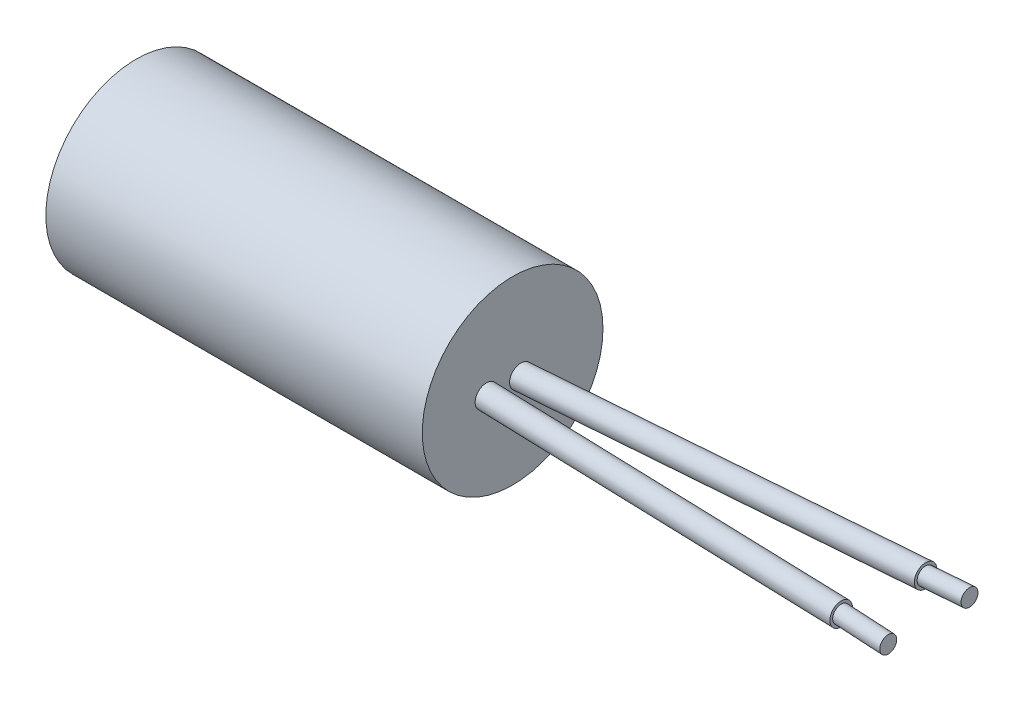
SolidWorks part; units mm, degrees
ref_plane "Front Plane" through (0, 0, 0) normal (0, 0, 1) x (1, 0, 0)
ref_plane "Top Plane" through (0, 0, 0) normal (0, 1, 0) x (1, 0, 0)
ref_plane "Right Plane" through (0, 0, 0) normal (1, 0, 0) x (0, 0, -1)
sketch "Sketch1" plane through (0, 0, 0) normal (1, 0, 0) x (0, 0, -1)
  circle A0 centre (0, 0) radius 4.8
  dimension "D1" = 9.6
extrude "Tube" add sketch "Sketch1" along normal blind 20
sketch "Sketch2" plane through (0, 0, 0) normal (0, 1, 0) x (1, 0, 0)
  line L0 (20, -4.8) -> (20, 4.8) construction
  line L2 (39.9389, 2) -> (39.9389, 0) construction
  line L3 (39.9389, 0) -> (39.9389, -3.1987) construction
  line L4 (39.9389, 0) -> (20, 0) construction
  spline S0 degree 1 poles (20, 0.4375) (39.9389, 2) knots 0 0 1 1
  dimension "D1" = 20
  dimension "D2" = 2
sketch "Sketch3" plane through (20, 0, 0) normal (1, 0, 0) x (0, 0, -1)
  circle A1 centre (0.4375, 0) radius 0.6
sweep "Sweep1" add profiles "Sketch3" path "Sketch2"
sketch "Sketch5" plane through (0, 0, 0) normal (0, 1, 0) x (1, 0, 0)
  line L0 (20, -1.3925) -> (39.4528, -2)
  line L1 (20, -4.8) -> (20, 4.8) construction
  line L2 (39.4528, -2) -> (39.4528, 0) construction
  line L3 (39.4528, 0) -> (20, 0) construction
  dimension "D1" = 2
sketch "Sketch6" plane through (20, 0, 0) normal (1, 0, 0) x (0, 0, -1)
  circle A0 centre (-1.3925, 0) radius 0.6
sweep "Sweep2" add profiles "Sketch6" path "Sketch5"
sketch "Sketch7" plane through (0, 0, 0) normal (0, 1, 0) x (1, 0, 0)
  line L0 (39.9389, 2) -> (52.6031, 2.9989)
  line L1 (39.9389, 1.4) -> (39.9389, 2.6) construction
sketch "Sketch8" plane through (0, 0, 0) normal (0, 1, 0) x (1, 0, 0)
  line L0 (39.4528, -2) -> (53.1023, -2.7643)
  line L1 (39.4528, -2.6) -> (39.4528, -1.4) construction
sketch "Sketch9" plane through (39.9389, 0, 0) normal (1, 0, 0) x (0, 0, -1)
  circle A0 centre (2, 0) radius 0.45
sketch "Sketch10" plane through (39.4528, 0, 0) normal (1, 0, 0) x (0, 0, -1)
  circle A0 centre (-2, 0) radius 0.45
sweep "ca" add profiles "Sketch9" path "Sketch7"
sweep "an" add profiles "Sketch10" path "Sketch8"
sketch "Sketch11" plane through (0, 0, 0) normal (0, 1, 0) x (1, 0, 0)
  line L1 (42.1027, 4.7643) -> (55.0536, 4.7643)
  line L2 (42.1027, 4.7643) -> (42.1027, -4.8197)
  line L3 (42.1027, -4.8197) -> (55.0536, -4.8197)
  line L4 (55.0536, 4.7643) -> (55.0536, -4.8197)
extrude "wire cut" cut sketch "Sketch11" against normal mid plane 10
equation "\"D\"=9.6"
equation "\"D1@Sketch1\"=\"D\""
equation "\"L\"=20"
equation "\"D1@Tube\"=\"L\""
